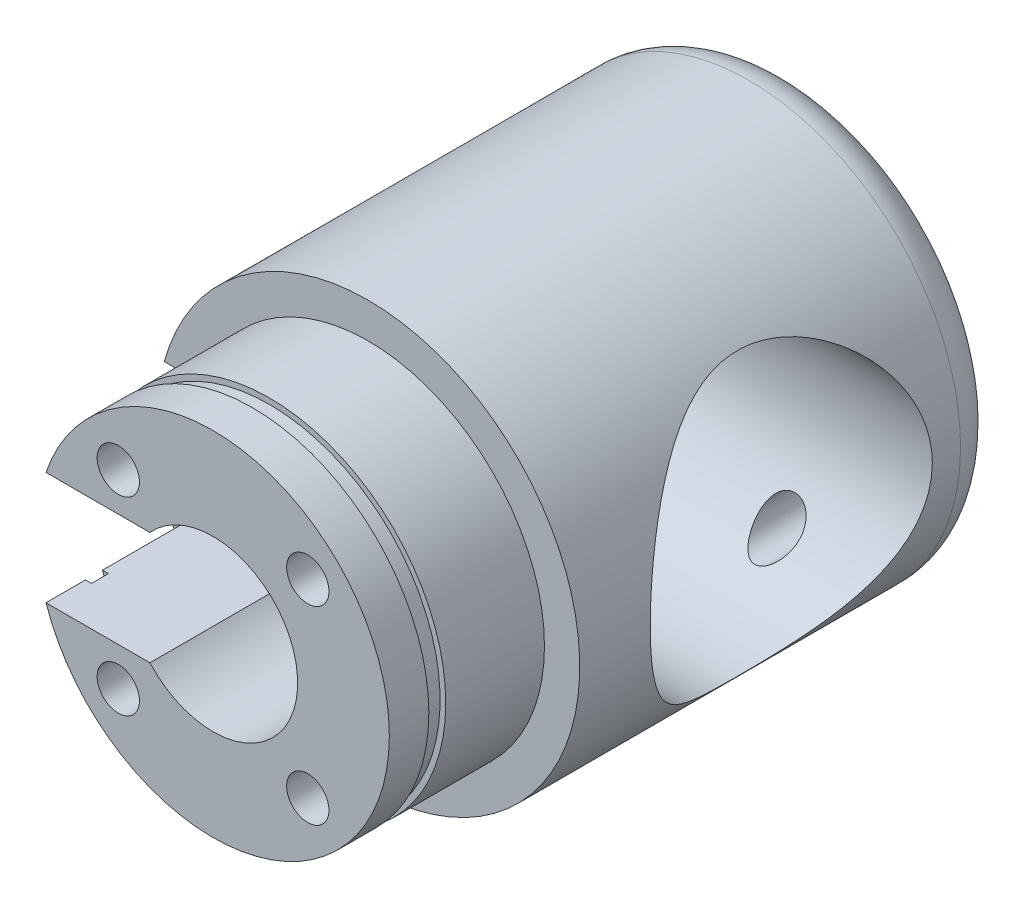
SolidWorks part; units mm, degrees
ref_plane "前视基准面" through (0, 0, 0) normal (0, 0, 1) x (1, 0, 0)
ref_plane "上视基准面" through (0, 0, 0) normal (0, 1, 0) x (1, 0, 0)
ref_plane "右视基准面" through (0, 0, 0) normal (1, 0, 0) x (0, 0, -1)
other "Configuration Table"
sketch "草图1" plane through (0, 0, 0) normal (0, 0, 1) x (1, 0, 0)
  circle A0 centre (0, 0) radius 12.5
  dimension "D1" = 25
extrude "凸台-拉伸1" add sketch "草图1" along normal blind 8
ref_plane "基准面1" through (0, 0, 0) normal (0, 0, -1) x (-1, 0, 0)
sketch "草图2" plane through (0, 0, 0) normal (0, 0, -1) x (-1, 0, 0)
  circle A0 centre (0, 0) radius 15
  dimension "D1" = 30
extrude "凸台-拉伸2" add sketch "草图2" along normal blind 30
sketch "草图3" plane through (0, 0, 0) normal (1, 0, 0) x (0, 0, -1)
  line L0 (0, 0) -> (30, 0)
  line L2 (30, -15) -> (30, 15) construction
  circle A0 centre (15, 0) radius 10
  dimension "D1" = 20
extrude "切除-拉伸1" cut sketch "草图3" against normal mid plane 30 contours A0
sketch "草图5" plane through (0, 0, 8) normal (0, 0, 1) x (1, 0, 0)
  circle A0 centre (0, 0) radius 12.5
extrude "凸台-拉伸3" add sketch "草图5" along normal blind 3
ref_plane "基准面2" through (0, 0, 7) normal (0, 0, 1) x (1, 0, 0)
sketch "草图6" plane through (0, 0, 7) normal (0, 0, 1) x (1, 0, 0)
  circle A0 centre (0, 0) radius 12.1
  circle A1 centre (0, 0) radius 12.5
  dimension "D1" = 24.2
extrude "切除-拉伸2" cut sketch "草图6" along normal blind 1.2
sketch "草图9" plane through (0, 0, 0) normal (0, 0, -1) x (-1, 0, 0)
  circle A0 centre (0, 0) radius 15
  circle A1 centre (0, 0) radius 15
  circle A2 centre (0, 0) radius 12.5
  dimension "D1" = 30
extrude "凸台-拉伸4" add sketch "草图9" along normal blind 2 contours A0 A2
sketch "草图12" plane through (0, 0, 11) normal (0, 0, 1) x (1, 0, 0)
  line L0 (0, 0) -> (9.5, 0) construction
  line L1 (0, 0) -> (15.1615, 15.1615) construction
  circle A1 centre (6.7175, 6.7175) radius 1.5
  circle A2 centre (6.7175, -6.7175) radius 1.5
  circle A3 centre (-6.7175, -6.7175) radius 1.5
  circle A4 centre (-6.7175, 6.7175) radius 1.5
  point P16 (0, 0)
  dimension "D3" = 3
  dimension "D2" = 45
  dimension "D4" = 9.5
  dimension "D5" = 4
extrude "切除-拉伸6" cut sketch "草图12" against normal through all
sketch "草图13" plane through (0, 0, 11) normal (0, 0, 1) x (1, 0, 0)
  circle A0 centre (0, 0) radius 6
  dimension "D1" = 12
extrude "切除-拉伸7" cut sketch "草图13" against normal blind 20
sketch "草图14" plane through (0, 0, 11) normal (0, 0, 1) x (1, 0, 0)
  line L1 (-0.7319, -4) -> (-24.2681, -4)
  line L2 (-0.7319, -4) -> (-0.7319, 4)
  line L3 (-0.7319, 4) -> (-24.2681, 4)
  line L4 (-24.2681, -4) -> (-24.2681, 4)
  line L5 (-0.7319, -4) -> (-24.2681, 4) construction
  line L6 (-0.7319, 4) -> (-24.2681, -4) construction
  circle A0 centre (0, 0) radius 12.5 construction
  circle A1 centre (0, 0) radius 12.5 construction
  point P0 (-12.5, 0)
  dimension "D1" = 8
extrude "切除-拉伸8" cut sketch "草图14" against normal blind 20
fillet "圆角1" radius 3 1 edges at (-15, 0, -30)
